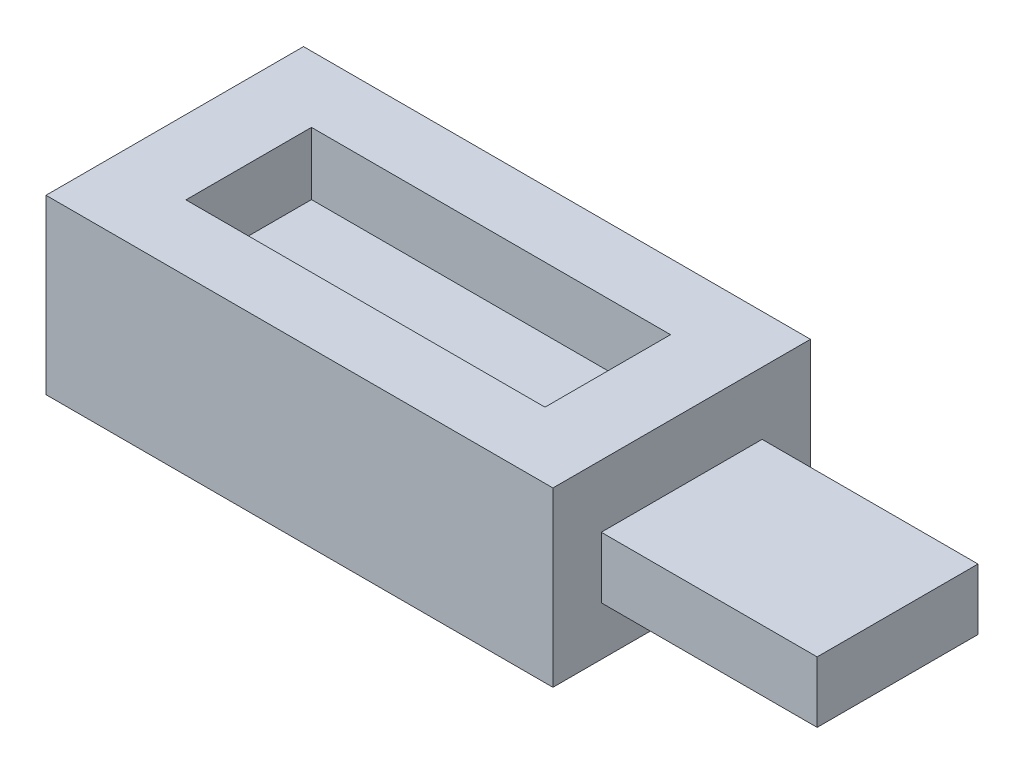
SolidWorks part; units mm, degrees
ref_plane "Front Plane" through (0, 0, 0) normal (0, 0, 1) x (1, 0, 0)
ref_plane "Top Plane" through (0, 0, 0) normal (0, 1, 0) x (1, 0, 0)
ref_plane "Right Plane" through (0, 0, 0) normal (1, 0, 0) x (0, 0, -1)
sketch "Sketch1" plane through (0, 0, 0) normal (0, 1, 0) x (1, 0, 0)
  line L1 (-102.8928, -52.2674) -> (102.8928, -52.2674)
  line L2 (-102.8928, -52.2674) -> (-102.8928, 52.2674)
  line L3 (-102.8928, 52.2674) -> (102.8928, 52.2674)
  line L4 (102.8928, -52.2674) -> (102.8928, 52.2674)
  line L5 (-102.8928, -52.2674) -> (102.8928, 52.2674) construction
  line L6 (-102.8928, 52.2674) -> (102.8928, -52.2674) construction
  point P0 (0, 0)
extrude "Boss-Extrude1" add sketch "Sketch1" along normal blind 70.104
sketch "Sketch2" plane through (0, 70.104, 0) normal (0, 1, 0) x (1, 0, 0)
  line L1 (-72.8794, -25.487) -> (72.8794, -25.487)
  line L2 (-72.8794, -25.487) -> (-72.8794, 25.487)
  line L3 (-72.8794, 25.487) -> (72.8794, 25.487)
  line L4 (72.8794, -25.487) -> (72.8794, 25.487)
  line L5 (-72.8794, -25.487) -> (72.8794, 25.487) construction
  line L6 (-72.8794, 25.487) -> (72.8794, -25.487) construction
  point P0 (0, 0)
extrude "Cut-Extrude1" cut sketch "Sketch2" against normal blind 25.4
sketch "Sketch3" plane through (102.8928, 0, 0) normal (1, 0, 0) x (0, 0, -1)
  line L1 (-32.6491, 19.9219) -> (32.6491, 19.9219)
  line L2 (-32.6491, 19.9219) -> (-32.6491, 44.7216)
  line L3 (-32.6491, 44.7216) -> (32.6491, 44.7216)
  line L4 (32.6491, 19.9219) -> (32.6491, 44.7216)
  line L5 (-32.6491, 19.9219) -> (32.6491, 44.7216) construction
  line L6 (-32.6491, 44.7216) -> (32.6491, 19.9219) construction
  point P0 (0, 32.3218)
extrude "Boss-Extrude2" add sketch "Sketch3" along normal blind 87.63
